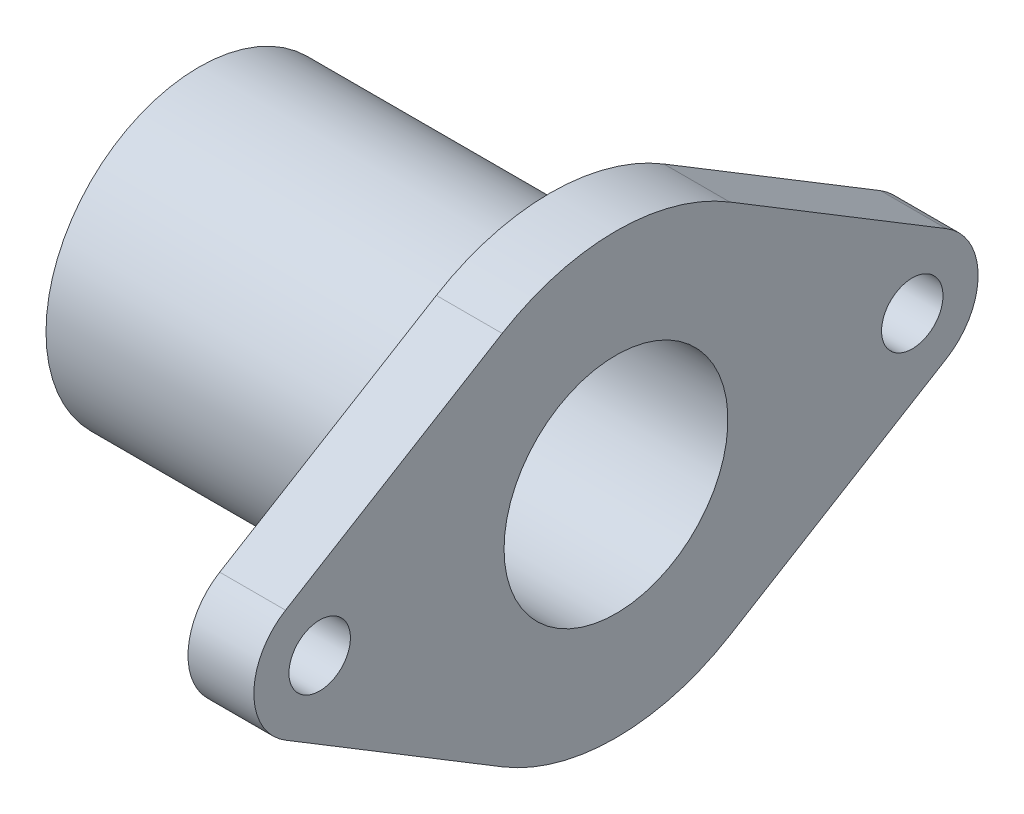
SolidWorks part; units mm, degrees
material "Cast Carbon Steel"
ref_plane "Front Plane" through (0, 0, 0) normal (0, 0, 1) x (1, 0, 0)
ref_plane "Top Plane" through (0, 0, 0) normal (0, 1, 0) x (1, 0, 0)
ref_plane "Right Plane" through (0, 0, 0) normal (1, 0, 0) x (0, 0, -1)
sketch "Sketch1" plane through (0, 0, 0) normal (1, 0, 0) x (0, 0, -1)
  line L0 (-25.9259, 42.7533) -> (-75.2778, 12.826)
  line L1 (25.9259, 42.7533) -> (75.2778, 12.826)
  line L2 (-75.2778, -12.826) -> (-25.9259, -42.7533)
  line L3 (75.2778, -12.826) -> (25.9259, -42.7533)
  arc A0 (25.9259, 42.7533) -> (-25.9259, 42.7533) centre (0, 0) ccw
  arc A1 (-75.2778, 12.826) -> (-75.2778, -12.826) centre (-67.5, 0) ccw
  arc A2 (75.2778, -12.826) -> (75.2778, 12.826) centre (67.5, 0) ccw
  arc A3 (-25.9259, -42.7533) -> (25.9259, -42.7533) centre (0, 0) ccw
  dimension "D1" = 100
  dimension "D2" = 30
  dimension "D3" = 30
  dimension "D4" = 67.5
  dimension "D5" = 67.5
extrude "Boss-Extrude1" add sketch "Sketch1" along normal blind 15
sketch "Sketch2" plane through (0, 0, 0) normal (-1, 0, 0) x (0, 0, 1)
  circle A0 centre (67.5, 0) radius 7
  circle A1 centre (-67.5, 0) radius 7
  dimension "D1" = 14
  dimension "D2" = 14
extrude "Cut-Extrude1" cut sketch "Sketch2" against normal through all
sketch "Sketch3" plane through (0, 0, 0) normal (-1, 0, 0) x (0, 0, 1)
  circle A0 centre (0, 0) radius 25.5
  dimension "D1" = 51
extrude "Cut-Extrude2" cut sketch "Sketch3" against normal through all
sketch "Sketch4" plane through (0, 0, 0) normal (-1, 0, 0) x (0, 0, 1)
  circle A0 centre (0, 0) radius 25.5
  circle A1 centre (0, 0) radius 34.85
  dimension "D1" = 51
  dimension "D2" = 69.7
extrude "Boss-Extrude2" add sketch "Sketch4" along normal blind 80
sketch "Sketch5" plane through (0, 0, 0) normal (0, 1, 0) x (1, 0, 0)
  line L0 (0, 34.85) -> (-5, 34.85)
  line L1 (0, 34.85) -> (-80, 34.85) construction
  line L2 (-5, 34.85) -> (0, 41.85)
  line L3 (0, 75.2778) -> (0, 25.9259) construction
  line L4 (0, 41.85) -> (0, 34.85)
  line L5 (0, 0) -> (-83.9507, 0) construction
  dimension "D1" = 5
  dimension "D2" = 7
revolve "Revolve1" add sketch "Sketch5" angle 360 about L5
